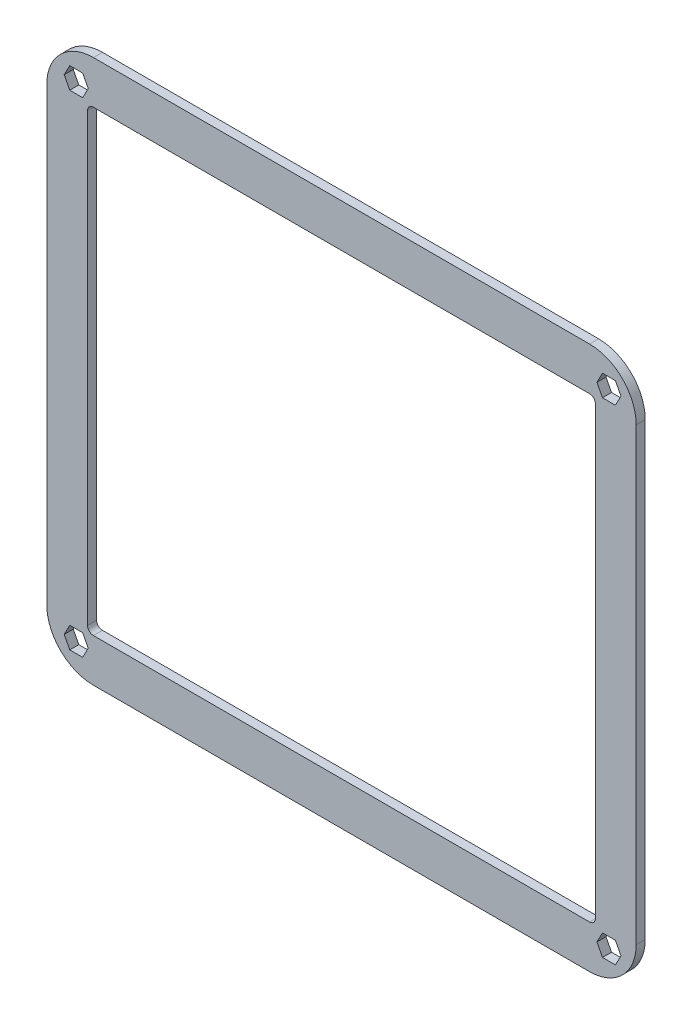
SolidWorks part; units mm, degrees
ref_plane "Ebene vorne" through (0, 0, 0) normal (0, 0, 1) x (1, 0, 0)
ref_plane "Ebene oben" through (0, 0, 0) normal (0, 1, 0) x (1, 0, 0)
ref_plane "Ebene rechts" through (0, 0, 0) normal (1, 0, 0) x (0, 0, -1)
sketch "Skizze1" plane through (0, 0, 0) normal (0, 0, 1) x (1, 0, 0)
  line L0 (-49.2275, -51.8905) -> (-49.2275, -151.2967) construction
  line L1 (-49.2275, -51.8905) -> (-49.2275, -151.2967)
  line L4 (-59.5275, -152.0967) -> (-169.0581, -152.0967) construction
  line L5 (-170.3518, -150.803) -> (-170.3518, -52.3842) construction
  line L6 (-59.5275, -152.0967) -> (-169.0581, -152.0967)
  line L7 (-170.3518, -150.803) -> (-170.3518, -52.3842)
  line L12 (-169.0581, -161.5967) -> (-59.5275, -161.5967)
  line L13 (-169.0581, -161.5967) -> (-59.5275, -161.5967)
  line L14 (-48.7338, -150.803) -> (-48.7338, -52.3842)
  line L16 (-179.3474, -52.3842) -> (-179.3474, -150.8036)
  line L17 (-179.3474, -52.3842) -> (-179.3474, -150.8036)
  line L18 (-58.2338, -52.3842) -> (-58.2338, -150.803) construction
  line L19 (-58.2338, -52.3842) -> (-58.2338, -150.803)
  line L151 (-57.8838, -155.0967) -> (-56.6591, -152.7467) construction
  line L153 (-56.6591, -157.4467) -> (-57.8838, -155.0967) construction
  line L182 (-53.8085, -157.4467) -> (-56.6591, -157.4467) construction
  line L183 (-52.5838, -155.0967) -> (-53.8085, -157.4467) construction
  line L186 (-59.5275, -41.5905) -> (-169.0581, -41.5905)
  line L217 (-59.5275, -41.5905) -> (-169.0581, -41.5905)
  line L219 (-53.8085, -152.7467) -> (-52.5838, -155.0967) construction
  line L220 (-56.6591, -152.7467) -> (-53.8085, -152.7467) construction
  line L233 (-171.4222, -157.4467) -> (-170.1974, -155.0967) construction
  line L234 (-174.2727, -157.4467) -> (-171.4222, -157.4467) construction
  line L235 (-175.4974, -155.0967) -> (-174.2727, -157.4467) construction
  line L236 (-174.2727, -152.7467) -> (-175.4974, -155.0967) construction
  line L237 (-171.4222, -152.7467) -> (-174.2727, -152.7467) construction
  line L238 (-170.1974, -155.0967) -> (-171.4222, -152.7467) construction
  line L251 (-175.4974, -48.0905) -> (-174.2727, -45.7405) construction
  line L252 (-174.2727, -50.4405) -> (-175.4974, -48.0905) construction
  line L253 (-171.4222, -50.4405) -> (-174.2727, -50.4405) construction
  line L254 (-170.1974, -48.0905) -> (-171.4222, -50.4405) construction
  line L255 (-171.4222, -45.7405) -> (-170.1974, -48.0905) construction
  line L256 (-174.2727, -45.7405) -> (-171.4222, -45.7405) construction
  line L281 (-57.8838, -48.0905) -> (-56.6591, -45.7405) construction
  line L282 (-56.6591, -50.4405) -> (-57.8838, -48.0905) construction
  line L283 (-53.8085, -50.4405) -> (-56.6591, -50.4405) construction
  line L284 (-52.5838, -48.0905) -> (-53.8085, -50.4405) construction
  line L513 (-53.8085, -45.7405) -> (-52.5838, -48.0905) construction
  line L515 (-56.6591, -45.7405) -> (-53.8085, -45.7405) construction
  line L673 (-57.8838, -155.0967) -> (-56.6591, -152.7467)
  line L674 (-56.6591, -157.4467) -> (-57.8838, -155.0967)
  line L675 (-53.8085, -157.4467) -> (-56.6591, -157.4467)
  line L676 (-52.5838, -155.0967) -> (-53.8085, -157.4467)
  line L677 (-53.8085, -152.7467) -> (-52.5838, -155.0967)
  line L678 (-56.6591, -152.7467) -> (-53.8085, -152.7467)
  line L679 (-171.4222, -157.4467) -> (-170.1974, -155.0967)
  line L680 (-174.2727, -157.4467) -> (-171.4222, -157.4467)
  line L681 (-175.4974, -155.0967) -> (-174.2727, -157.4467)
  line L682 (-174.2727, -152.7467) -> (-175.4974, -155.0967)
  line L683 (-171.4222, -152.7467) -> (-174.2727, -152.7467)
  line L684 (-170.1974, -155.0967) -> (-171.4222, -152.7467)
  line L685 (-175.4974, -48.0905) -> (-174.2727, -45.7405)
  line L686 (-174.2727, -50.4405) -> (-175.4974, -48.0905)
  line L687 (-171.4222, -50.4405) -> (-174.2727, -50.4405)
  line L688 (-170.1974, -48.0905) -> (-171.4222, -50.4405)
  line L689 (-171.4222, -45.7405) -> (-170.1974, -48.0905)
  line L690 (-174.2727, -45.7405) -> (-171.4222, -45.7405)
  line L691 (-57.8838, -48.0905) -> (-56.6591, -45.7405)
  line L692 (-56.6591, -50.4405) -> (-57.8838, -48.0905)
  line L693 (-53.8085, -50.4405) -> (-56.6591, -50.4405)
  line L694 (-52.5838, -48.0905) -> (-53.8085, -50.4405)
  line L695 (-53.8085, -45.7405) -> (-52.5838, -48.0905)
  line L696 (-56.6591, -45.7405) -> (-53.8085, -45.7405)
  line L700 (-59.5275, -51.0905) -> (-169.0581, -51.0905) construction
  line L704 (-59.5275, -51.0905) -> (-169.0581, -51.0905)
  arc A0 (-59.5275, -161.5967) -> (-49.2275, -151.2967) centre (-59.5275, -151.2967) ccw construction
  arc A1 (-49.2275, -51.8905) -> (-59.5275, -41.5905) centre (-59.5275, -51.8905) ccw construction
  arc A2 (-59.5275, -161.5967) -> (-49.2275, -151.2967) centre (-59.5275, -151.2967) ccw
  arc A3 (-49.2275, -51.8905) -> (-59.5275, -41.5905) centre (-59.5275, -51.8905) ccw
  arc A4 (-170.3518, -150.803) -> (-169.0581, -152.0967) centre (-169.0581, -150.803) ccw construction
  arc A5 (-169.0581, -51.0905) -> (-170.3518, -52.3842) centre (-169.0581, -52.3842) ccw construction
  arc A6 (-58.2338, -52.3842) -> (-59.5275, -51.0905) centre (-59.5275, -52.3842) ccw construction
  arc A7 (-170.3518, -150.803) -> (-169.0581, -152.0967) centre (-169.0581, -150.803) ccw
  arc A16 (-59.5275, -161.5967) -> (-48.7338, -150.803) centre (-59.5275, -150.803) ccw
  arc A18 (-48.7338, -52.3842) -> (-59.5275, -41.5905) centre (-59.5275, -52.3842) ccw
  arc A20 (-169.0581, -41.5905) -> (-179.3474, -52.3842) centre (-169.0581, -51.8916) ccw
  arc A21 (-169.0581, -41.5905) -> (-179.3474, -52.3842) centre (-169.0581, -51.8916) ccw
  arc A22 (-179.3474, -150.8036) -> (-169.0581, -161.5967) centre (-169.0581, -151.2956) ccw
  arc A23 (-179.3474, -150.8036) -> (-169.0581, -161.5967) centre (-169.0581, -151.2956) ccw
  arc A24 (-169.0581, -51.0905) -> (-170.3518, -52.3842) centre (-169.0581, -52.3842) ccw
  arc A25 (-58.2338, -52.3842) -> (-59.5275, -51.0905) centre (-59.5275, -52.3842) ccw
  arc A26 (-59.5275, -152.0967) -> (-58.2338, -150.803) centre (-59.5275, -150.803) ccw construction
  arc A27 (-59.5275, -152.0967) -> (-58.2338, -150.803) centre (-59.5275, -150.803) ccw
  dimension "D1" = 0
extrude "Aufsatz-Linear austragen1" add sketch "Skizze1" along normal blind 2
